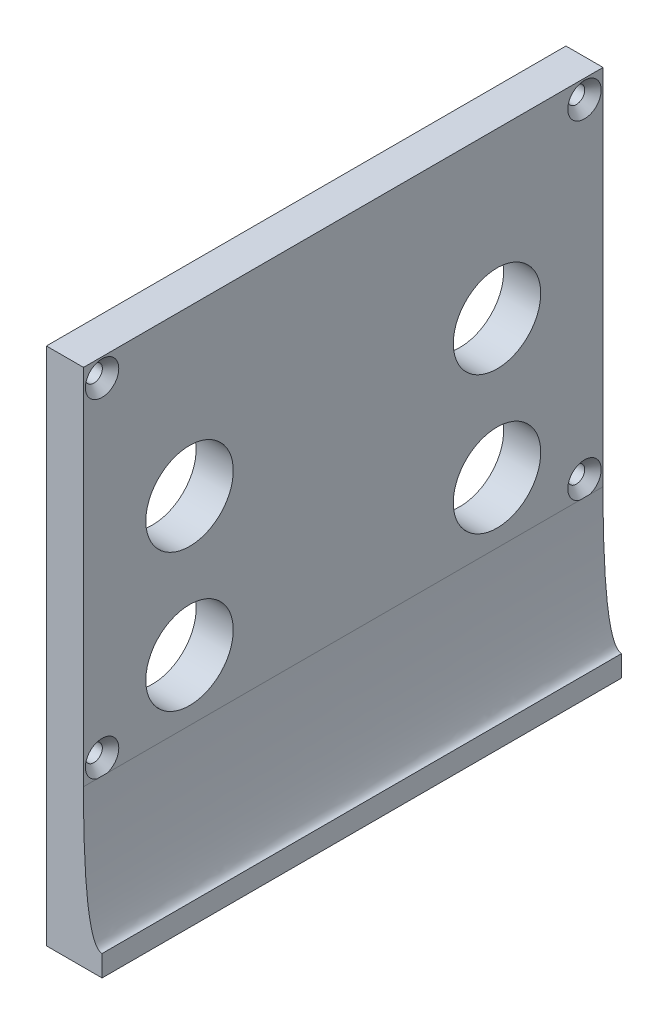
SolidWorks part; units mm, degrees
ref_plane "Front Plane" through (0, 0, 0) normal (0, 0, 1) x (1, 0, 0)
ref_plane "Top Plane" through (0, 0, 0) normal (0, 1, 0) x (1, 0, 0)
ref_plane "Right Plane" through (0, 0, 0) normal (1, 0, 0) x (0, 0, -1)
sketch "Sketch1" plane through (0, 0, 0) normal (0, 0, 1) x (1, 0, 0)
  line L0 (-46.8387, 41.5675) -> (-46.8387, -56.4325)
  line L1 (-46.8387, -56.4325) -> (-36.3387, -56.4325)
  line L2 (-36.3387, -56.4325) -> (-36.3387, -52.4325)
  line L3 (-46.8387, 41.5675) -> (-39.8387, 41.5675)
  line L4 (-39.8387, 41.5675) -> (-39.8387, -26.9325)
  line L5 (-39.8387, -26.9325) -> (-39.8387, -52.4325) construction
  line L6 (-39.8387, -52.4325) -> (-36.3387, -52.4325) construction
  spline S0 degree 2 poles (-39.8387, -26.9325) (-39.8387, -52.4325) (-36.3387, -52.4325) knots 0 0 0 1 1 1
extrude "Boss-Extrude1" add sketch "Sketch1" along normal blind 98
sketch "Sketch2" plane through (-46.8387, 0, 0) normal (-1, 0, 0) x (0, 0, 1)
  line L0 (0, 41.5675) -> (20, 41.5675) construction
  line L1 (98, 41.5675) -> (0, 41.5675) construction
  line L2 (20, 41.5675) -> (20, 10.5675) construction
  line L3 (20, 10.5675) -> (20, -15.4325) construction
  line L4 (98, 41.5675) -> (78, 41.5675) construction
  line L5 (78, 41.5675) -> (78, 10.5675) construction
  line L6 (78, 10.5675) -> (78, -15.4325) construction
  circle A0 centre (20, 10.5675) radius 8.25
  circle A1 centre (78, 10.5675) radius 8.25
  circle A2 centre (78, -15.4325) radius 8.25
  circle A3 centre (20, -15.4325) radius 8.25
  dimension "D1" = 20
  dimension "D2" = 31
  dimension "D3" = 26
  dimension "D4" = 20
  dimension "D5" = 31
  dimension "D6" = 26
extrude "Cut-Extrude1" cut sketch "Sketch2" against normal through all contours A0 | A2 | A1 | A3
sketch "Sketch6" plane through (-39.8387, 0, 0) normal (1, 0, 0) x (0, 0, -1)
  line L0 (-98, 41.5675) -> (-94.5, 41.5675) construction
  line L1 (-98, 41.5675) -> (0, 41.5675) construction
  line L2 (-94.5, 41.5675) -> (-94.5, 38.0675) construction
  line L3 (-94.5, 38.0675) -> (-94.5, -23.9325) construction
  line L4 (-94.5, -23.9325) -> (-3.5, -23.9325) construction
  line L5 (-3.5, -23.9325) -> (-3.5, 38.0675) construction
hole_wizard "CSK for M3 Flat Head Machine Screw2" positions "Sketch7" profile "Sketch8" countersink size "M3" standard "ANSI Metric"
sketch "Sketch7" plane through (-39.8387, 0, 0) normal (1, 0, 0) x (0, 0, -1)
  point P0 (-94.5, 38.0675)
  point P3 (-94.5, -23.9325)
  point P6 (-3.5, -23.9325)
  point P9 (-3.5, 38.0675)
sketch "Sketch8" plane through (-39.8387, 38.0675, 94.5) normal (0, 1, 0) x (0, 0, -1)
  line L0 (0, 0) -> (0, 10.9614)
  line L1 (0, 10.9614) -> (1.6, 10)
  line L2 (1.6, 10) -> (1.6, 1.55)
  line L3 (1.6, 1.55) -> (3.15, 0)
  line L5 (3.15, 0) -> (0, 0)
  line L6 (-1.6, 1.55) -> (-3.15, 0) construction
  line L10 (0, 10.9614) -> (-1.6, 10) construction
  line L11 (0, -6.35) -> (0, 107.95) construction
  dimension "Hole Dia." = 3.2
  dimension "Hole Depth" = 10
  dimension "Near C'Sink Dia." = 6.3
  dimension "Near C'Sink Angle" = 90
  dimension "Drill Angle" = 118
sketch "Sketch9" plane through (-46.8387, 0, 0) normal (-1, 0, 0) x (0, 0, 1)
  line L0 (49, 41.5675) -> (39.5, 41.5675) construction
  line L1 (39.5, 41.5675) -> (39.5, 40.0675) construction
  line L3 (39.5, 40.0675) -> (69, 40.0675)
  line L4 (39.5, 40.0675) -> (39.5, 33.0675)
  line L5 (39.5, 33.0675) -> (69, 33.0675)
  line L6 (69, 40.0675) -> (69, 33.0675)
extrude "Cut-Extrude2" cut sketch "Sketch9" against normal blind 2.5
